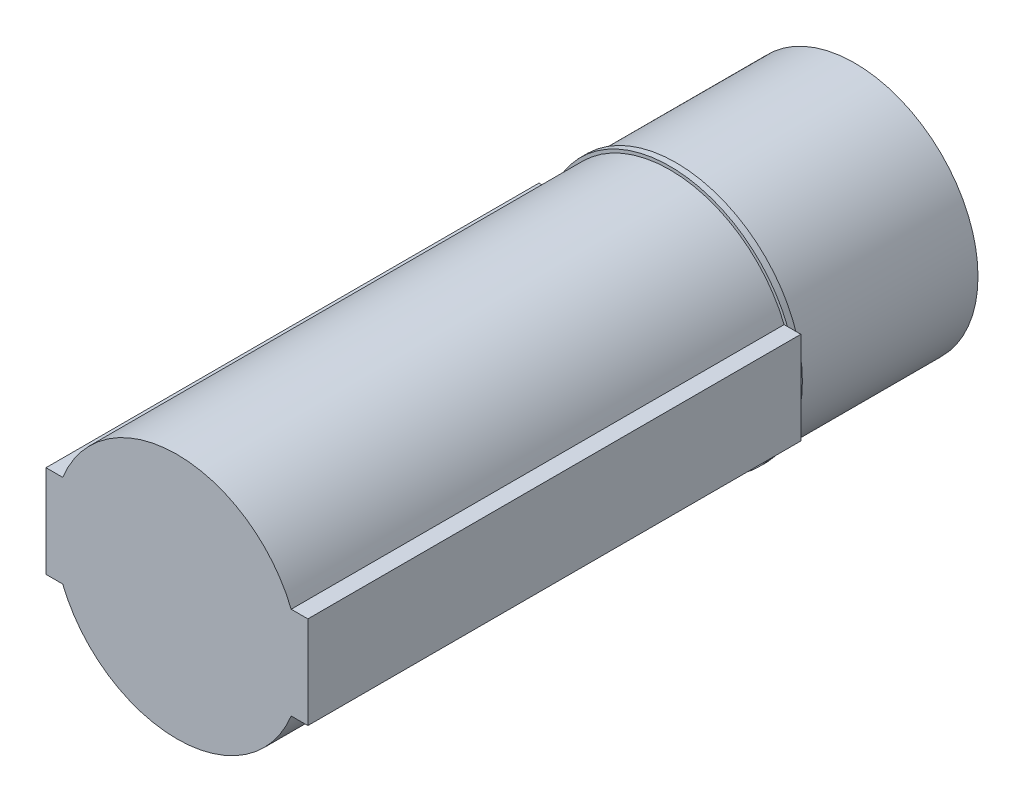
SolidWorks part; units mm, degrees
ref_plane "Front Plane" through (0, 0, 0) normal (0, 0, 1) x (1, 0, 0)
ref_plane "Top Plane" through (0, 0, 0) normal (0, 1, 0) x (1, 0, 0)
ref_plane "Right Plane" through (0, 0, 0) normal (1, 0, 0) x (0, 0, -1)
sketch "Sketch1" plane through (0, 0, 0) normal (0, 0, 1) x (1, 0, 0)
  line L0 (0.9978, 1.12) -> (0.9978, -1.12)
  circle A0 centre (0, 0) radius 2
  arc A1 (0.9978, 1.12) -> (0.9978, -1.12) centre (0, 0) ccw
  dimension "D1" = 4
  dimension "D3" = 3
  dimension "D2" = 2.24
extrude "Boss-Extrude1" add sketch "Sketch1" along normal blind 7
sketch "Sketch2" plane through (0, 0, 0) normal (0, 0, 1) x (1, 0, 0)
  circle A0 centre (0, 0) radius 2.05
  circle A1 centre (0, 0) radius 2
  dimension "D1" = 4.1
extrude "Boss-Extrude3" add sketch "Sketch2" along normal blind 3
sketch "Sketch3" plane through (0, 0, 0) normal (0, 0, 1) x (1, 0, 0)
  circle A0 centre (0, 0) radius 2.05
  circle A1 centre (0, 0) radius 2
extrude "Cut-Extrude1" cut sketch "Sketch3" along normal blind 2.9
sketch "Sketch4" plane through (0, 0, 7) normal (0, 0, 1) x (1, 0, 0)
  line L0 (1.854, 0.75) -> (2.125, 0.75)
  line L1 (-2.125, -0.75) -> (-1.854, -0.75)
  line L2 (-2.125, -0.75) -> (-2.125, 0.75)
  line L3 (-2.125, 0.75) -> (-1.854, 0.75)
  line L4 (2.125, -0.75) -> (2.125, 0.75)
  line L5 (-2.125, -0.75) -> (2.125, 0.75) construction
  line L6 (-2.125, 0.75) -> (2.125, -0.75) construction
  line L7 (1.854, -0.75) -> (2.125, -0.75)
  arc A0 (-1.854, -0.75) -> (1.854, -0.75) centre (0, 0) ccw
  arc A1 (1.854, 0.75) -> (-1.854, 0.75) centre (0, 0) ccw
  dimension "D3" = 4
  dimension "D1" = 4.25
  dimension "D2" = 1.5
extrude "Boss-Extrude4" add sketch "Sketch4" along normal blind 4
sketch "Sketch8" plane through (0, 0, 11) normal (0, 0, 1) x (1, 0, 0)
  line L0 (1.854, -0.75) -> (2.125, -0.75) construction
  line L1 (2.125, 0.75) -> (1.854, 0.75) construction
  line L2 (2.125, -0.75) -> (2.125, 0.75) construction
  line L3 (-2.125, -0.75) -> (-1.854, -0.75) construction
  line L4 (-2.125, 0.75) -> (-2.125, -0.75) construction
  line L5 (-1.854, 0.75) -> (-2.125, 0.75) construction
  line L6 (1.854, -0.75) -> (2.125, -0.75)
  line L7 (2.125, 0.75) -> (1.854, 0.75)
  line L8 (2.125, -0.75) -> (2.125, 0.75)
  line L9 (-2.125, -0.75) -> (-1.854, -0.75)
  line L10 (-2.125, 0.75) -> (-2.125, -0.75)
  line L11 (-1.854, 0.75) -> (-2.125, 0.75)
  arc A1 (-1.854, 0.75) -> (-1.854, -0.75) centre (0, 0) ccw
  arc A2 (1.854, -0.75) -> (1.854, 0.75) centre (0, 0) ccw
extrude "Boss-Extrude5" add sketch "Sketch8" against normal blind 8
